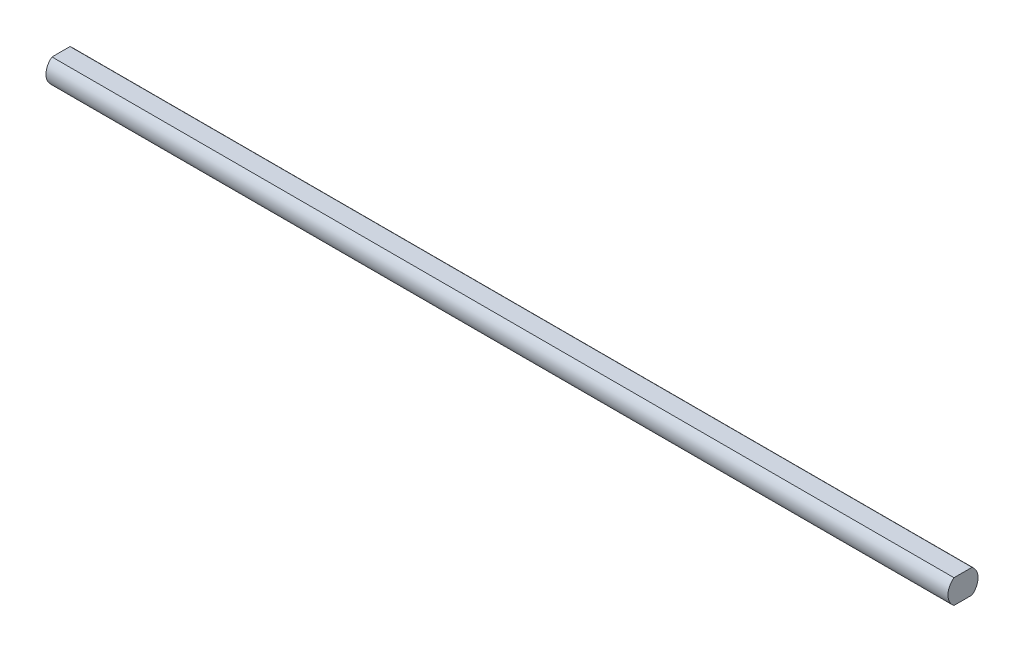
SolidWorks part; units mm, degrees
ref_plane "Front Plane" through (0, 0, 0) normal (0, 0, 1) x (1, 0, 0)
ref_plane "Top Plane" through (0, 0, 0) normal (0, 1, 0) x (1, 0, 0)
ref_plane "Right Plane" through (0, 0, 0) normal (1, 0, 0) x (0, 0, -1)
sketch "Sketch1" plane through (0, 0, 0) normal (0, 0, 1) x (1, 0, 0)
  line L0 (-150, 0) -> (150, 0)
  line L1 (150, 0) -> (150, -5)
  line L2 (150, -5) -> (-150, -5)
  line L3 (-150, -5) -> (-150, 0)
  dimension "D1" = 5
  dimension "D2" = 300
revolve "Revolve1" add sketch "Sketch1" angle 360 about L0
sketch "Sketch2" plane through (150, 0, 0) normal (1, 0, 0) x (0, 0, -1)
  line L0 (-3, 4) -> (3, 4)
  line L1 (0, 0) -> (2.6931, 0) construction
  line L2 (-3, -4) -> (3, -4)
  arc A0 (-3, 4) -> (3, 4) centre (0, 0) cw
  circle A1 centre (0, 0) radius 5 construction
  arc A2 (-3, -4) -> (3, -4) centre (0, 0) ccw
  point P3 (0, 5)
  circle M4 centre (0, 0) radius 5
  dimension "D1" = 1
extrude "Cut-Extrude1" cut sketch "Sketch2" against normal up to surface (300 mm away) contours L2 M4 | A0 L0 up to face at (-150, 0, 5)
